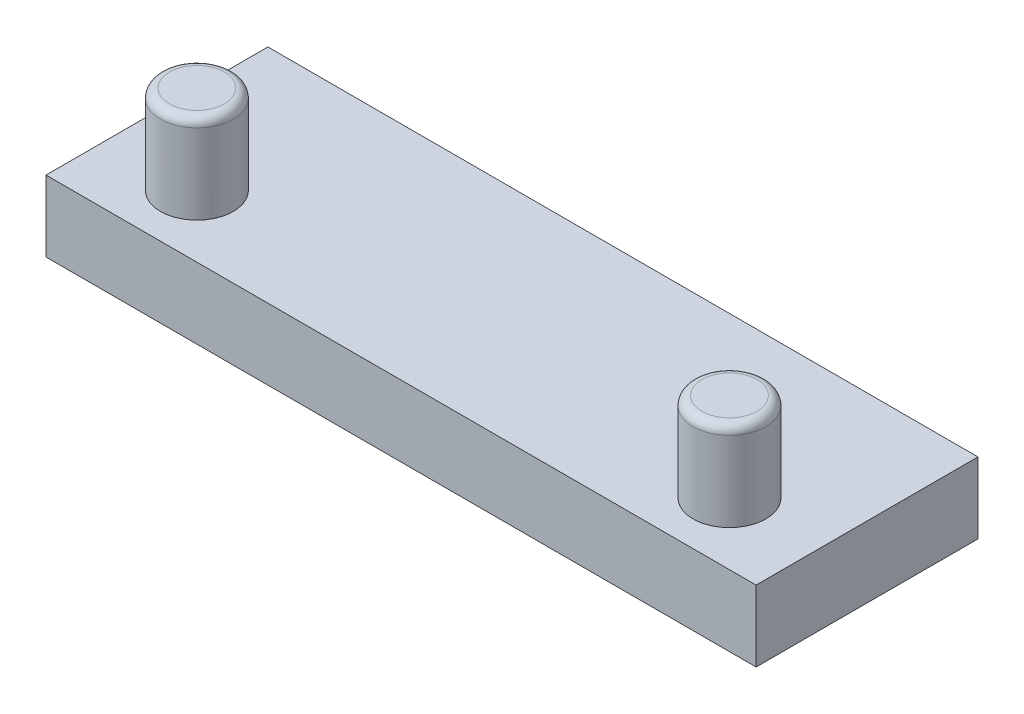
SolidWorks part; units mm, degrees
ref_plane "前视基准面" through (0, 0, 0) normal (0, 0, 1) x (1, 0, 0)
ref_plane "上视基准面" through (0, 0, 0) normal (0, 1, 0) x (1, 0, 0)
ref_plane "右视基准面" through (0, 0, 0) normal (1, 0, 0) x (0, 0, -1)
sketch "草图1" plane through (0, 0, 0) normal (0, 0, 1) x (1, 0, 0)
  line L0 (-10, 0) -> (10, 0)
  line L1 (10, 0) -> (10, 10)
  line L2 (10, 10) -> (-10, 10)
  line L3 (-10, 10) -> (-10, 0)
  line L4 (-5, 3) -> (5, 3) construction
  circle A0 centre (-5, 3) radius 1.5
  circle A1 centre (5, 3) radius 1.5
  point P3 (0, 0)
  point P10 (0, 3)
  dimension "D3" = 3
  dimension "D4" = 3
  dimension "D1" = 20
  dimension "D2" = 10
  dimension "D5" = 10
extrude "凸台-拉伸1" add sketch "草图1" along normal blind 5
sketch "草图2" plane through (0, 10, 0) normal (0, 1, 0) x (1, 0, 0)
  line L1 (-20, 0) -> (20, 0)
  line L2 (-20, 0) -> (-20, -12.5)
  line L3 (-20, -12.5) -> (20, -12.5)
  line L4 (20, 0) -> (20, -12.5)
  line L5 (10, -5) -> (-10, -5) construction
  point P4 (0, 0)
  dimension "D1" = 7.5
  dimension "D2" = 40
extrude "凸台-拉伸2" add sketch "草图2" against normal blind 4
sketch "草图3" plane through (0, 10, 0) normal (0, 1, 0) x (1, 0, 0)
  line L0 (-15, -9) -> (15, -9) construction
  circle A0 centre (-15, -9) radius 2.05
  circle A1 centre (15, -9) radius 2.05
  point P4 (0, -9)
  dimension "D1" = 30
  dimension "D2" = 4.1
  dimension "D3" = 9
extrude "凸台-拉伸3" add sketch "草图3" along normal blind 5
fillet "圆角1" radius 0.5 2 edges at (12.95, 15, 9) (-17.05, 15, 9)
